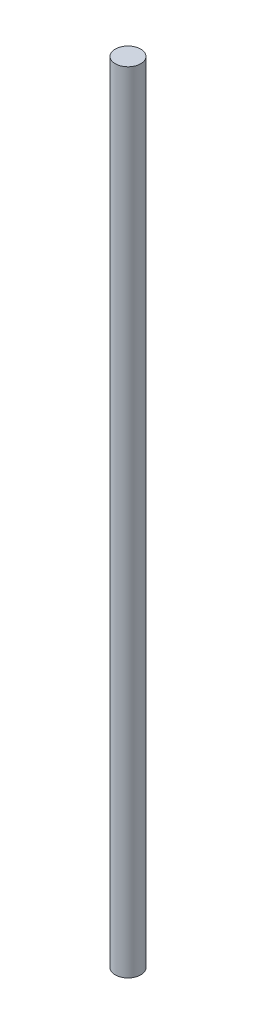
SolidWorks part; units mm, degrees
material "1060 合金"
ref_plane "前视基准面" through (0, 0, 0) normal (0, 0, 1) x (1, 0, 0)
ref_plane "上视基准面" through (0, 0, 0) normal (0, 1, 0) x (1, 0, 0)
ref_plane "右视基准面" through (0, 0, 0) normal (1, 0, 0) x (0, 0, -1)
other "Configuration Table"
sketch "草图1" plane through (0, 0, 0) normal (0, 1, 0) x (1, 0, 0)
  circle A0 centre (0, 0) radius 1
  dimension "D1" = 2
extrude "凸台-拉伸1" add sketch "草图1" along normal blind 62
